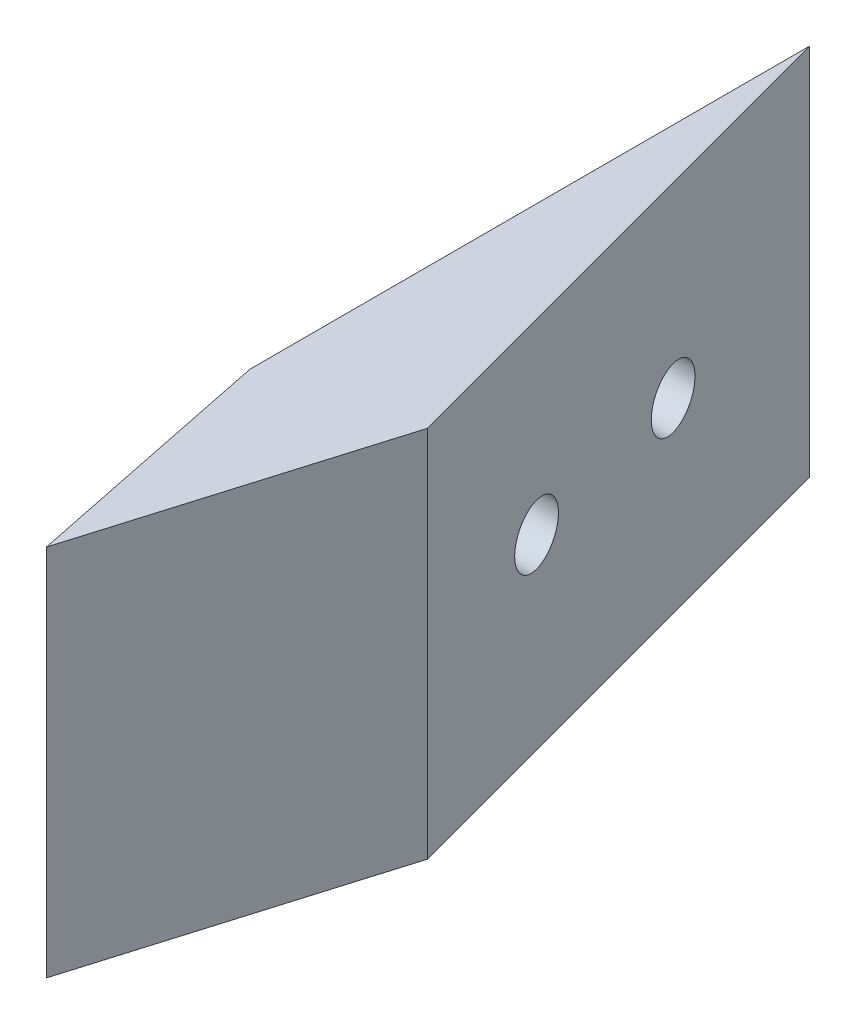
SolidWorks part; units mm, degrees
ref_plane "前视基准面" through (0, 0, 0) normal (0, 0, 1) x (1, 0, 0)
ref_plane "上视基准面" through (0, 0, 0) normal (0, 1, 0) x (1, 0, 0)
ref_plane "右视基准面" through (0, 0, 0) normal (1, 0, 0) x (0, 0, -1)
other "Configuration Table"
sketch "草图2" plane through (0, 0, 0) normal (0, 1, 0) x (1, 0, 0)
  line L15 (-2.5, 0) -> (2.5, 0)
  line L16 (-2.5, 0) -> (-2.5, -32)
  line L17 (-2.5, -32) -> (2.5, -32)
  line L18 (2.5, 0) -> (2.5, -32)
  dimension "D1" = 5
  dimension "D2" = 32
extrude "凸台-拉伸1" add sketch "草图2" along normal blind 10
sketch "草图3" plane through (0, 10, 0) normal (0, 1, 0) x (1, 0, 0)
  line L0 (-2.5, 0) -> (7.4104, -36.9862)
  line L2 (-2.5, 0) -> (-2.5, -32) construction
  line L3 (-2.5, -15) -> (1.25, -13.9952)
  line L4 (1.25, -13.9952) -> (-1.1, -21.8586)
  line L6 (-2.5, -15) -> (-1.1, -21.8586)
  point P2 (0, 0)
  point P8 (-3.4256, -7.0611)
  point P9 (-7.0394, -1.4255)
  point P11 (-5.338, -1.0969)
  point P12 (-0.8765, -4.1349)
  point P13 (-5.1026, -2.2501)
  point P16 (-4.2026, -6.6589)
  point P17 (0, 0)
  line M10 (-2.5, 0) -> (-2.5, -32)
  line M11 (-2.5, -32) -> (2.5, -32)
  line M12 (2.5, -32) -> (2.5, 0)
  line M13 (2.5, 0) -> (-2.5, 0)
  dimension "D1" = 15
  dimension "D2" = 3.8823
  dimension "D3" = 7
  dimension "D4" = 28.176
extrude "切除-拉伸1" cut sketch "草图3" against normal through all contours L6 L0 L4 M10 M11 M12 | L0 M13 M12
sketch "草图4" plane through (-2.5, 0, 0) normal (-1, 0, 0) x (0, 0, 1)
  line L0 (0, 10) -> (0, 0) construction
  line L1 (15, 0) -> (15, 10) construction
  circle A0 centre (5, 5) radius 0.8
  circle A1 centre (10, 5) radius 0.8
  point P4 (0, 0)
  point P5 (0, 0)
  point P8 (0, 5)
  dimension "D1" = 1.6
  dimension "D2" = 5
  dimension "D3" = 5
extrude "切除-拉伸2" cut sketch "草图4" against normal through all
